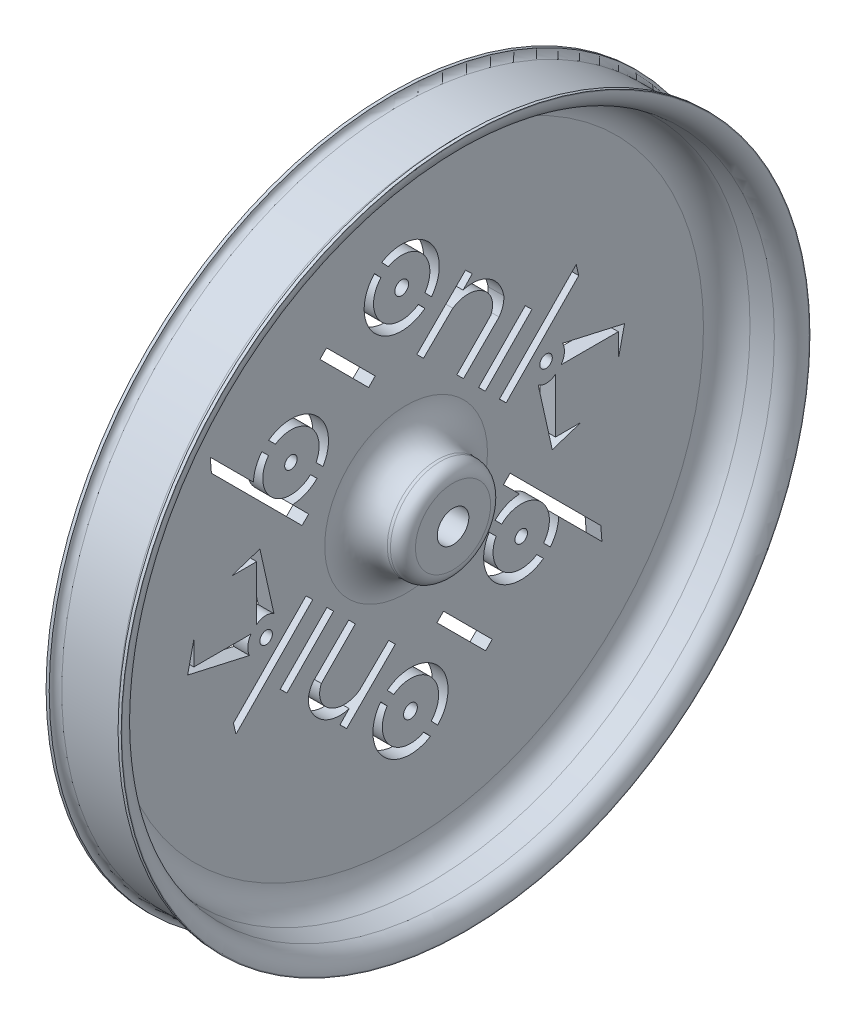
SolidWorks part; units mm, degrees
ref_plane "Płaszczyzna przednia" through (0, 0, 0) normal (0, 0, 1) x (1, 0, 0)
ref_plane "Płaszczyzna górna" through (0, 0, 0) normal (0, 1, 0) x (1, 0, 0)
ref_plane "Płaszczyzna prawa" through (0, 0, 0) normal (1, 0, 0) x (0, 0, -1)
sketch "Szkic1" plane through (0, 0, 0) normal (0, 0, 1) x (1, 0, 0)
  line L0 (7.5, -25.7789) -> (-2.5, -25.7789)
  line L1 (7.5, -25.7789) -> (7.5, -17.7789)
  line L2 (7.5, -17.7789) -> (0, -17.7789)
  line L3 (0, -17.7789) -> (0, 21.719)
  line L4 (-2.5, 29.2211) -> (-2, 29.2211)
  line L5 (9.5, 29.2211) -> (9.5, 29.1143)
  line L6 (9.5, 29.2211) -> (9, 29.2211)
  line L7 (-2, 29.2211) -> (-2, 29.2183)
  line L8 (-1, 28.2183) -> (8, 28.2183)
  line L9 (-2.5, 29.2211) -> (-2.5, -25.7789)
  line L10 (3.4713, 25.6839) -> (6.8965, 26.1406)
  line L11 (9, 29.2183) -> (9, 29.2211)
  arc A0 (-1, 28.2183) -> (-2, 29.2183) centre (-1, 29.2183) cw
  arc A1 (9.5, 29.1143) -> (6.8965, 26.1406) centre (6.5, 29.1143) cw
  arc A2 (0, 21.719) -> (3.4713, 25.6839) centre (4, 21.719) cw
  arc A3 (8, 28.2183) -> (9, 29.2183) centre (8, 29.2183) ccw
  point P10 (9.5, 26.2211)
  point P17 (0, 27.2211)
  dimension "D6" = 0.5
  dimension "D9" = 3
  dimension "D10" = 4
  dimension "D12" = 1
  dimension "D1" = 10
  dimension "D2" = 8
  dimension "D3" = 55
  dimension "D4" = 12
  dimension "D5" = 3
  dimension "D7" = 0.5
  dimension "D8" = 45
  dimension "D11" = 2.5
revolve "Obrót1" add sketch "Szkic1" angle 360 about L0
sketch "Szkic4" plane through (7.5, 0, 0) normal (1, 0, 0) x (0, 0, -1)
  circle A0 centre (0, -25.7789) radius 2.525
  dimension "D1" = 5.05
extrude "Wytnij-wyciągnięcie8" cut sketch "Szkic4" against normal through all
sketch "Szkic5" plane through (0, 0, 0) normal (1, 0, 0) x (0, 0, -1)
  line L0 (112.1629, 275.1146) -> (679.4962, 275.1146) construction
  line L1 (-31.0948, -6.6131) -> (-16.6157, -21.0922)
  line L2 (-16.6157, -21.0922) -> (-15.5551, -20.0316)
  line L3 (-15.5551, -20.0316) -> (-18.1257, -17.4609)
  line L4 (-24.3831, -11.2036) -> (-31.2774, -4.3092)
  line L5 (-31.2774, -4.3092) -> (-31.0948, -6.6131)
  line L6 (-13.7626, 0.4627) -> (-12.702, 1.5234)
  line L7 (-12.702, 1.5234) -> (-4.9238, -6.2548)
  line L8 (-4.9238, -6.2548) -> (-5.9844, -7.3154)
  line L9 (-5.9844, -7.3154) -> (-13.7626, 0.4627)
  line L10 (2.7778, -7.6585) -> (1.7172, -6.5979)
  line L11 (1.7172, -6.5979) -> (9.4953, 1.1803)
  line L12 (9.4953, 1.1803) -> (10.57, 0.1339)
  line L13 (10.57, 0.1339) -> (9.0927, -1.3833)
  line L14 (2.7778, -7.6585) -> (7.4664, -3.0724)
  line L15 (14.8516, -7.9843) -> (9.168, -13.6679)
  line L16 (9.168, -13.6679) -> (8.1073, -12.6072)
  line L17 (8.1073, -12.6072) -> (13.5313, -7.0832)
  line L18 (19.0342, -8.5077) -> (20.1045, -9.5586)
  line L19 (20.1045, -9.5586) -> (12.6512, -17.1495)
  line L20 (12.6512, -17.1495) -> (11.5808, -16.0986)
  line L21 (11.5808, -16.0986) -> (19.0342, -8.5077)
  line L22 (14.91, -19.3675) -> (27.173, -6.8781)
  line L23 (27.173, -6.8781) -> (27.5713, -8.6134)
  line L24 (27.5713, -8.6134) -> (15.9803, -20.4184)
  line L25 (15.9803, -20.4184) -> (14.91, -19.3675)
  line L30 (25.0179, -16.6923) -> (34.8909, -18.9183)
  line L31 (34.8909, -18.9183) -> (33.8934, -23.3427)
  line L32 (33.8934, -23.3427) -> (33.8934, -19.5403)
  line L33 (33.8934, -19.5403) -> (24.7607, -19.5403)
  line L34 (21.1025, -20.5215) -> (23.3499, -30.5953)
  line L35 (23.3499, -30.5953) -> (27.9255, -29.0986)
  line L36 (27.9255, -29.0986) -> (23.865, -29.0986)
  line L37 (23.865, -29.0986) -> (23.865, -20.3921)
  line L38 (-14.2148, -15.7768) -> (-15.2757, -14.716)
  line L39 (-13.2714, -14.599) -> (-14.3731, -13.4973)
  line L40 (-21.9663, -8.7368) -> (-23.0341, -7.669)
  line L41 (-20.8696, -7.7122) -> (-21.9465, -6.6352)
  line L42 (-2.824, 7.8162) -> (-3.8882, 8.9319)
  line L43 (-4.0153, 6.8919) -> (-5.0523, 7.9791)
  line L44 (3.009, 1.3009) -> (4.0611, 0.1978)
  line L45 (1.9645, 0.2227) -> (3.0062, -0.8694)
  arc A0 (-2.824, 7.8162) -> (3.009, 1.3009) centre (-0.7, 3.8491) cw
  circle A1 centre (-18.3888, -11.4667) radius 1
  arc A2 (-4.0153, 6.8919) -> (1.9645, 0.2227) centre (-0.7, 3.8491) ccw
  circle A3 centre (-0.7, 3.8491) radius 1.1
  arc A6 (7.4664, -3.0724) -> (12.8569, -3.5397) centre (9.8742, -6.6212) cw
  arc A7 (9.0927, -1.3833) -> (15.6101, -5.4316) centre (10.5698, -6.2757) cw
  arc A8 (12.8569, -3.5397) -> (13.5313, -7.0832) centre (10.6785, -5.7902) cw
  arc A9 (15.6101, -5.4316) -> (14.8516, -7.9843) centre (11.6962, -5.6576) cw
  circle A10 centre (22.3514, -17.8482) radius 1
  arc A11 (25.0179, -16.6923) -> (24.7607, -19.5403) centre (22.4645, -17.8973) cw
  arc A12 (23.865, -20.3921) -> (21.1025, -20.5215) centre (22.3975, -18.6134) cw
  arc A13 (-23.0341, -7.669) -> (-24.3831, -11.2036) centre (-18.3888, -11.4667) ccw
  arc A14 (-21.9465, -6.6352) -> (-13.2714, -14.599) centre (-18.3888, -11.4667) cw
  arc A15 (-14.3731, -13.4973) -> (-20.8696, -7.7122) centre (-18.3888, -11.4667) ccw
  arc A16 (-21.9663, -8.7368) -> (-15.2757, -14.716) centre (-18.3888, -11.4667) ccw
  arc A17 (-14.2148, -15.7768) -> (-18.1257, -17.4609) centre (-18.3888, -11.4667) cw
  arc A18 (-3.8882, 8.9319) -> (4.0611, 0.1978) centre (-0.7, 3.8491) cw
  arc A19 (-5.0523, 7.9791) -> (3.0062, -0.8694) centre (-0.7, 3.8491) ccw
  point P71 (-1, -15)
  dimension "D11" = 1.5
  dimension "D12" = 2
  dimension "D13" = 2
  dimension "D14" = 1.5
  dimension "D15" = 1.5
  dimension "D19" = 11
  dimension "D23" = 1.5
  dimension "D24" = 1.5
  dimension "D25" = 6
  dimension "D26" = 6
  dimension "D1" = 1.5
  dimension "D2" = 1.5
  dimension "D5" = 1.5
  dimension "D6" = 1.5
  dimension "D7" = 1.5
  dimension "D8" = 1.5
  dimension "D9" = 1.5
  dimension "D10" = 1.5
  dimension "D16" = 1.5
  dimension "D17" = 1.5
  dimension "D18" = 1.5
  dimension "D20" = 11
  dimension "D21" = 10.6384
  dimension "D22" = 1.5
  dimension "D27" = 0.524
extrude "Wytnij-wyciągnięcie9" cut sketch "Szkic5" against normal through all
fillet "Zaokrąglenie1" radius 2 1 edges at (7.5, -25.7789, -8)
sketch "Szkic6" plane through (0, 0, 0) normal (1, 0, 0) x (0, 0, -1)
  line L35 (-20.6685, -60.7541) -> (-20.6685, -65.2374)
  line L36 (-20.6685, -65.2374) -> (-19.6852, -65.2374)
  line L37 (-19.6852, -65.2374) -> (-19.6852, -62.7584)
  line L38 (-19.729, -61.5951) -> (-19.6986, -61.5951)
  line L39 (-19.5465, -62.2204) -> (-18.3908, -65.2374)
  line L40 (-18.3908, -65.2374) -> (-17.4985, -65.2374)
  line L41 (-17.4985, -65.2374) -> (-16.3631, -62.1893)
  line L42 (-16.211, -61.5951) -> (-16.184, -61.5951)
  line L43 (-16.2244, -62.5549) -> (-16.2244, -65.2374)
  line L44 (-16.2244, -65.2374) -> (-15.1462, -65.2374)
  line L45 (-15.1462, -65.2374) -> (-15.1462, -60.7541)
  line L46 (-15.1462, -60.7541) -> (-16.7043, -60.7541)
  line L47 (-16.7043, -60.7541) -> (-17.6946, -63.4053)
  line L48 (-17.8871, -64.0525) -> (-17.9075, -64.0525)
  line L49 (-18.08, -63.4117) -> (-19.0699, -60.7541)
  line L50 (-19.0699, -60.7541) -> (-20.6685, -60.7541)
  line L51 (-12.801, -60.7541) -> (-14.565, -65.2374)
  line L52 (-14.565, -65.2374) -> (-13.3822, -65.2374)
  line L53 (-13.3822, -65.2374) -> (-13.041, -64.2401)
  line L54 (-13.041, -64.2401) -> (-11.3174, -64.2401)
  line L55 (-11.3174, -64.2401) -> (-10.9726, -65.2374)
  line L56 (-10.9726, -65.2374) -> (-9.7831, -65.2374)
  line L57 (-9.7831, -65.2374) -> (-11.5066, -60.7541)
  line L58 (-11.5066, -60.7541) -> (-12.801, -60.7541)
  line L59 (-8.7022, -60.7541) -> (-7.2894, -62.9959)
  line L60 (-7.2894, -62.9959) -> (-8.8338, -65.2374)
  line L61 (-8.8338, -65.2374) -> (-7.5327, -65.2374)
  line L62 (-7.5327, -65.2374) -> (-6.6945, -63.79)
  line L63 (-6.5829, -63.4774) -> (-6.5695, -63.4774)
  line L64 (-6.4716, -63.7776) -> (-5.6367, -65.2374)
  line L65 (-5.6367, -65.2374) -> (-4.3423, -65.2374)
  line L66 (-4.3423, -65.2374) -> (-5.8363, -62.9771)
  line L67 (-5.8363, -62.9771) -> (-4.3828, -60.7541)
  line L68 (-4.3828, -60.7541) -> (-5.5996, -60.7541)
  line L69 (-5.5996, -60.7541) -> (-6.37, -62.0859)
  line L70 (-6.5221, -62.4768) -> (-6.5358, -62.4768)
  line L71 (-6.6812, -62.0987) -> (-7.374, -60.7541)
  line L72 (-7.374, -60.7541) -> (-8.7022, -60.7541)
  line L73 (-2.5549, -60.7541) -> (-2.5549, -65.2374)
  line L74 (-2.5549, -65.2374) -> (-0.693, -65.2374)
  line L75 (-0.0506, -62.8302) -> (-0.0506, -62.8177)
  line L76 (-0.7909, -60.7541) -> (-2.5549, -60.7541)
  line L77 (4.4336, -60.7541) -> (2.6693, -65.2374)
  line L78 (2.6693, -65.2374) -> (3.8521, -65.2374)
  line L79 (3.8521, -65.2374) -> (4.1936, -64.2401)
  line L80 (4.1936, -64.2401) -> (5.9172, -64.2401)
  line L81 (5.9172, -64.2401) -> (6.2618, -65.2374)
  line L82 (6.2618, -65.2374) -> (7.4516, -65.2374)
  line L83 (7.4516, -65.2374) -> (5.728, -60.7541)
  line L84 (5.728, -60.7541) -> (4.4336, -60.7541)
  line L85 (8.877, -60.7541) -> (8.877, -63.3429)
  line L86 (12.8853, -63.2961) -> (12.8853, -60.7541)
  line L87 (12.8853, -60.7541) -> (11.7937, -60.7541)
  line L88 (11.7937, -60.7541) -> (11.7937, -63.3928)
  line L89 (9.9723, -63.3554) -> (9.9723, -60.7541)
  line L90 (9.9723, -60.7541) -> (8.877, -60.7541)
  line L91 (14.9702, -60.7541) -> (14.9702, -65.2374)
  line L92 (14.9702, -65.2374) -> (15.9537, -65.2374)
  line L93 (15.9537, -65.2374) -> (15.9537, -62.7584)
  line L94 (15.9096, -61.5951) -> (15.9401, -61.5951)
  line L95 (16.0921, -62.2204) -> (17.2482, -65.2374)
  line L96 (17.2482, -65.2374) -> (18.1402, -65.2374)
  line L97 (18.1402, -65.2374) -> (19.2759, -62.1893)
  line L98 (19.4279, -61.5951) -> (19.455, -61.5951)
  line L99 (19.4142, -62.5549) -> (19.4142, -65.2374)
  line L100 (19.4142, -65.2374) -> (20.4924, -65.2374)
  line L101 (20.4924, -65.2374) -> (20.4924, -60.7541)
  line L102 (20.4924, -60.7541) -> (18.9343, -60.7541)
  line L103 (18.9343, -60.7541) -> (17.9443, -63.4053)
  line L104 (17.7515, -64.0525) -> (17.7314, -64.0525)
  line L105 (17.559, -63.4117) -> (16.5687, -60.7541)
  line L106 (16.5687, -60.7541) -> (14.9702, -60.7541)
  line L107 (-1.4634, -61.4983) -> (-1.0546, -61.4983)
  line L108 (-0.9834, -62.5613) -> (-1.4634, -62.5613)
  line L109 (-1.4634, -62.5613) -> (-1.4634, -61.4983)
  line L110 (-12.1961, -61.5546) -> (-12.169, -61.5546)
  line L111 (-12.0878, -61.9579) -> (-11.5674, -63.4649)
  line L112 (-11.5674, -63.4649) -> (-12.8077, -63.4649)
  line L113 (-12.8077, -63.4649) -> (-12.2807, -61.9454)
  line L114 (5.0385, -61.5546) -> (5.0656, -61.5546)
  line L115 (5.1465, -61.9579) -> (5.6672, -63.4649)
  line L116 (5.6672, -63.4649) -> (4.4266, -63.4649)
  line L117 (4.4266, -63.4649) -> (4.954, -61.9454)
  line L118 (-1.4634, -63.3116) -> (-0.8651, -63.3116)
  line L119 (-0.8721, -64.4935) -> (-1.4634, -64.4935)
  line L120 (-1.4634, -64.4935) -> (-1.4634, -63.3116)
  spline S29 degree 3 poles (-19.6852, -62.7584) (-19.6863, -62.6412) (-19.6885, -62.3946) (-19.7038, -62.0067) (-19.7203, -61.7363) (-19.729, -61.5951) knots 0 0 0 0 0.302027 0.635343 1 1 1 1
  spline S30 degree 3 poles (-19.6986, -61.5951) (-19.6777, -61.6928) (-19.6418, -61.8605) (-19.5944, -62.07) (-19.5596, -62.1793) (-19.5465, -62.2204) knots 0 0 0 0 0.465921 0.79909 1 1 1 1
  spline S31 degree 3 poles (-16.3631, -62.1893) (-16.3469, -62.1406) (-16.3091, -62.0272) (-16.2606, -61.8282) (-16.2287, -61.6783) (-16.211, -61.5951) knots 0 0 0 0 0.250853 0.584012 1 1 1 1
  spline S32 degree 3 poles (-16.184, -61.5951) (-16.192, -61.7084) (-16.2076, -61.9282) (-16.2215, -62.2483) (-16.2235, -62.455) (-16.2244, -62.5549) knots 0 0 0 0 0.354704 0.68797 1 1 1 1
  spline S33 degree 3 poles (-17.6946, -63.4053) (-17.7173, -63.4698) (-17.7649, -63.6052) (-17.8284, -63.8213) (-17.867, -63.9733) (-17.8871, -64.0525) knots 0 0 0 0 0.303823 0.637003 1 1 1 1
  spline S34 degree 3 poles (-17.9075, -64.0525) (-17.921, -63.9809) (-17.9481, -63.8368) (-18.006, -63.6226) (-18.0552, -63.4824) (-18.08, -63.4117) knots 0 0 0 0 0.329002 0.661877 1 1 1 1
  spline S35 degree 3 poles (-6.6945, -63.79) (-6.6771, -63.7475) (-6.6457, -63.6709) (-6.6071, -63.5669) (-6.5902, -63.5043) (-6.5829, -63.4774) knots 0 0 0 0 0.414756 0.747814 1 1 1 1
  spline S36 degree 3 poles (-6.5695, -63.4774) (-6.5588, -63.521) (-6.5398, -63.5987) (-6.5093, -63.7001) (-6.4828, -63.7546) (-6.4716, -63.7776) knots 0 0 0 0 0.425946 0.758455 1 1 1 1
  spline S37 degree 3 poles (-6.37, -62.0859) (-6.3924, -62.1388) (-6.4329, -62.2345) (-6.4846, -62.3645) (-6.5107, -62.4427) (-6.5221, -62.4768) knots 0 0 0 0 0.410263 0.743484 1 1 1 1
  spline S38 degree 3 poles (-6.5358, -62.4768) (-6.5502, -62.4302) (-6.5778, -62.3406) (-6.6259, -62.2141) (-6.6632, -62.1361) (-6.6812, -62.0987) knots 0 0 0 0 0.360592 0.693428 1 1 1 1
  spline S39 degree 3 poles (-0.693, -65.2374) (-0.5222, -65.2304) (-0.2015, -65.2172) (0.2487, -65.1035) (0.4922, -64.9507) (0.6081, -64.8779) knots 0 0 0 0 0.373882 0.702052 1 1 1 1
  spline S40 degree 3 poles (0.6081, -64.8779) (0.7033, -64.7935) (0.8897, -64.6282) (1.0527, -64.2791) (1.0983, -63.9384) (1.0635, -63.6326) (0.9571, -63.3815) (0.8359, -63.2505) (0.7739, -63.1836) knots 0 0 0 0 0.196043 0.384151 0.584354 0.724031 0.858939 1 1 1 1
  spline S41 degree 3 poles (0.7739, -63.1836) (0.7003, -63.1231) (0.5494, -62.999) (0.264, -62.8813) (0.0574, -62.8477) (-0.0506, -62.8302) knots 0 0 0 0 0.312152 0.640149 1 1 1 1
  spline S42 degree 3 poles (-0.0506, -62.8177) (0.0366, -62.791) (0.2062, -62.739) (0.4375, -62.6115) (0.5631, -62.4963) (0.6252, -62.4393) knots 0 0 0 0 0.348857 0.67836 1 1 1 1
  spline S43 degree 3 poles (0.6252, -62.4393) (0.6783, -62.3781) (0.7819, -62.2587) (0.8732, -62.0373) (0.9041, -61.7787) (0.8637, -61.4951) (0.7078, -61.2193) (0.4508, -61.0073) (0.1088, -60.8572) (-0.3152, -60.7679) (-0.6241, -60.759) (-0.7909, -60.7541) knots 0 0 0 0 0.082794 0.161272 0.24114 0.347886 0.449253 0.558501 0.683554 0.829073 1 1 1 1
  spline S44 degree 3 poles (8.877, -63.3429) (8.902, -63.7261) (8.9478, -64.4281) (9.7681, -65.2358) (10.8627, -65.3596) (11.9652, -65.2343) (12.8118, -64.4089) (12.8594, -63.6886) (12.8853, -63.2961) knots 0 0 0 0 0.174138 0.319064 0.493285 0.672816 0.82168 1 1 1 1
  spline S45 degree 3 poles (11.7937, -63.3928) (11.7841, -63.594) (11.7669, -63.9521) (11.4054, -64.3907) (10.888, -64.4718) (10.3655, -64.3877) (9.9991, -63.9327) (9.9819, -63.5635) (9.9723, -63.3554) knots 0 0 0 0 0.186157 0.331278 0.493092 0.658063 0.807295 1 1 1 1
  spline S46 degree 3 poles (15.9537, -62.7584) (15.9527, -62.6412) (15.9504, -62.3946) (15.9349, -62.0067) (15.9183, -61.7363) (15.9096, -61.5951) knots 0 0 0 0 0.302025 0.635343 1 1 1 1
  spline S47 degree 3 poles (15.9401, -61.5951) (15.961, -61.6928) (15.9969, -61.8605) (16.0442, -62.07) (16.079, -62.1793) (16.0921, -62.2204) knots 0 0 0 0 0.465921 0.79909 1 1 1 1
  spline S48 degree 3 poles (19.2759, -62.1893) (19.2921, -62.1406) (19.3298, -62.0272) (19.3784, -61.8282) (19.4102, -61.6783) (19.4279, -61.5951) knots 0 0 0 0 0.250853 0.584012 1 1 1 1
  spline S49 degree 3 poles (19.455, -61.5951) (19.4469, -61.7084) (19.4313, -61.9282) (19.4172, -62.2483) (19.4152, -62.455) (19.4142, -62.5549) knots 0 0 0 0 0.354705 0.687973 1 1 1 1
  spline S50 degree 3 poles (17.9443, -63.4053) (17.9216, -63.4698) (17.874, -63.6052) (17.8103, -63.8213) (17.7717, -63.9733) (17.7515, -64.0525) knots 0 0 0 0 0.303822 0.63702 1 1 1 1
  spline S51 degree 3 poles (17.7314, -64.0525) (17.718, -63.9809) (17.6908, -63.8368) (17.633, -63.6226) (17.5838, -63.4824) (17.559, -63.4117) knots 0 0 0 0 0.329002 0.661877 1 1 1 1
  spline S52 degree 3 poles (-1.0546, -61.4983) (-0.9058, -61.5032) (-0.6527, -61.5115) (-0.3168, -61.6834) (-0.2429, -61.9528) (-0.2697, -62.1549) (-0.3374, -62.3027) (-0.4507, -62.4192) (-0.6, -62.5033) (-0.782, -62.5535) (-0.9134, -62.5586) (-0.9834, -62.5613) knots 0 0 0 0 0.214019 0.36393 0.502152 0.581744 0.655624 0.731407 0.811388 0.899454 1 1 1 1
  spline S53 degree 3 poles (-12.169, -61.5546) (-12.1632, -61.6044) (-12.1519, -61.6995) (-12.1256, -61.8346) (-12.1, -61.9181) (-12.0878, -61.9579) knots 0 0 0 0 0.364666 0.697373 1 1 1 1
  spline S54 degree 3 poles (-12.2807, -61.9454) (-12.2668, -61.9024) (-12.2393, -61.8172) (-12.2108, -61.6863) (-12.201, -61.5984) (-12.1961, -61.5546) knots 0 0 0 0 0.337951 0.670517 1 1 1 1
  spline S55 degree 3 poles (5.0656, -61.5546) (5.0714, -61.6044) (5.0826, -61.6995) (5.1088, -61.8346) (5.1343, -61.9181) (5.1465, -61.9579) knots 0 0 0 0 0.364696 0.697382 1 1 1 1
  spline S56 degree 3 poles (4.954, -61.9454) (4.9678, -61.9024) (4.9953, -61.8172) (5.0238, -61.6863) (5.0336, -61.5984) (5.0385, -61.5546) knots 0 0 0 0 0.337951 0.670517 1 1 1 1
  spline S57 degree 3 poles (-0.8651, -63.3116) (-0.787, -63.3144) (-0.6412, -63.3195) (-0.44, -63.3699) (-0.2768, -63.4555) (-0.1528, -63.5721) (-0.0778, -63.7215) (-0.0572, -63.8897) (-0.0782, -64.0602) (-0.1538, -64.2168) (-0.2794, -64.34) (-0.4443, -64.4311) (-0.6472, -64.4851) (-0.7938, -64.4906) (-0.8721, -64.4935) knots 0 0 0 0 0.104446 0.194774 0.274999 0.348588 0.41889 0.493869 0.572366 0.645747 0.721977 0.804087 0.89532 1 1 1 1
sketch "Szkic7" plane through (0, 0, 0) normal (1, 0, 0) x (0, 0, -1)
  line L0 (-17.4603, -58.4263) -> (-17.4603, -54.0791)
  line L1 (-16.7503, -53.4132) -> (-14.2301, -54.0581)
  line L2 (-13.7698, -54.7242) -> (-13.7698, -54.7641)
  line L3 (-12.8433, -55.7872) -> (-6.3839, -55.7872)
  line L4 (-5.8713, -53.9113) -> (-8.3671, -52.0829)
  line L5 (-8.8797, -51.9124) -> (-11.4373, -51.9124)
  line L6 (-12.0226, -51.2308) -> (-12.0226, -49.2733)
  line L7 (-11.4373, -48.5916) -> (-8.8797, -48.5916)
  line L8 (-8.3671, -48.421) -> (-5.8713, -46.5928)
  line L9 (-6.3839, -44.7169) -> (-12.8433, -44.7169)
  line L10 (-13.7698, -45.7401) -> (-13.7698, -45.7801)
  line L11 (-14.2301, -46.446) -> (-16.7503, -47.0909)
  line L12 (-17.4603, -46.4248) -> (-17.4603, -42.0778)
  line L13 (-16.8751, -41.396) -> (-2.3518, -41.396)
  line L14 (-1.7668, -42.0778) -> (-1.7668, -47.7836)
  line L15 (-2.1038, -48.401) -> (-3.8125, -49.3352)
  line L16 (-3.8125, -51.1689) -> (-2.1038, -52.1031)
  line L17 (-1.7668, -52.7203) -> (-1.7668, -58.4263)
  line L18 (-2.3518, -59.1081) -> (-16.8751, -59.1081)
  line L25 (12.5072, -46.2896) -> (11.043, -45.1383)
  line L26 (0.5889, -41.2253) -> (6.712, -41.2253)
  line L27 (3.9645, -46.0591) -> (3.9645, -54.4452)
  line L28 (8.9311, -41.2253) -> (11.5375, -41.2253)
  line L29 (12.9545, -54.4452) -> (12.9545, -47.2104)
  line L30 (-0.5824, -58.1073) -> (-0.5824, -42.3968)
  line L31 (8.9311, -44.8876) -> (10.3191, -44.8876)
  line L32 (12.263, -41.4772) -> (17.0556, -45.2579)
  line L33 (17.5015, -46.1776) -> (17.5015, -58.1073)
  line L34 (5.136, -44.8876) -> (6.712, -44.8876)
  line L35 (6.712, -41.2253) -> (6.712, -44.8876)
  line L36 (8.9311, -41.2253) -> (8.9311, -44.8876)
  line L37 (6.712, -55.6165) -> (6.712, -59.2788)
  line L38 (8.9311, -55.6165) -> (8.9311, -59.2788)
  line L39 (5.136, -55.6165) -> (6.712, -55.6165)
  line L40 (8.9311, -55.6165) -> (11.7831, -55.6165)
  line L41 (16.3301, -59.2788) -> (8.9311, -59.2788)
  line L42 (6.712, -59.2788) -> (0.5889, -59.2788)
  spline S0 degree 3 poles (-16.8751, -59.1081) (-16.9789, -59.0879) (-17.1908, -59.0468) (-17.4157, -58.7696) (-17.445, -58.5441) (-17.4603, -58.4263) knots 0 0 0 0 0.314204 0.64159 1 1 1 1
  spline S1 degree 3 poles (-17.4603, -54.0791) (-17.445, -53.9603) (-17.4158, -53.7331) (-17.1921, -53.4681) (-16.9656, -53.3923) (-16.8345, -53.3983) (-16.7921, -53.4035) (-16.7643, -53.41) (-16.7503, -53.4132) knots 0 0 0 0 0.317625 0.607402 0.885007 0.922973 0.961318 1 1 1 1
  spline S2 degree 3 poles (-14.2301, -54.0581) (-14.1457, -54.0952) (-13.9729, -54.1712) (-13.8045, -54.4258) (-13.7816, -54.6226) (-13.7698, -54.7242) knots 0 0 0 0 0.315646 0.646724 1 1 1 1
  spline S3 degree 3 poles (-13.7698, -54.7641) (-13.7452, -54.9417) (-13.6975, -55.285) (-13.3367, -55.6982) (-13.0069, -55.7577) (-12.8433, -55.7872) knots 0 0 0 0 0.350775 0.677934 1 1 1 1
  spline S4 degree 3 poles (-6.3839, -55.7872) (-6.2194, -55.7577) (-5.888, -55.6982) (-5.5401, -55.2851) (-5.4303, -54.8291) (-5.4908, -54.432) (-5.6303, -54.1278) (-5.7914, -53.983) (-5.8713, -53.9113) knots 0 0 0 0 0.195604 0.394266 0.607256 0.741861 0.87198 1 1 1 1
  spline S5 degree 3 poles (-8.3671, -52.0829) (-8.4191, -52.0494) (-8.5221, -51.9829) (-8.698, -51.924) (-8.8191, -51.9162) (-8.8797, -51.9124) knots 0 0 0 0 0.337913 0.669074 1 1 1 1
  spline S6 degree 3 poles (-11.4373, -51.9124) (-11.541, -51.8922) (-11.753, -51.8511) (-11.978, -51.574) (-12.0073, -51.3486) (-12.0226, -51.2308) knots 0 0 0 0 0.31426 0.641681 1 1 1 1
  spline S7 degree 3 poles (-12.0226, -49.2733) (-12.0073, -49.1555) (-11.978, -48.93) (-11.753, -48.6529) (-11.541, -48.6117) (-11.4373, -48.5916) knots 0 0 0 0 0.35832 0.685765 1 1 1 1
  spline S8 degree 3 poles (-8.8797, -48.5916) (-8.8191, -48.5877) (-8.698, -48.58) (-8.5221, -48.5211) (-8.4191, -48.4546) (-8.3671, -48.421) knots 0 0 0 0 0.330905 0.662031 1 1 1 1
  spline S9 degree 3 poles (-5.8713, -46.5928) (-5.7914, -46.521) (-5.6304, -46.3762) (-5.4908, -46.0721) (-5.4303, -45.675) (-5.5401, -45.2191) (-5.8879, -44.8059) (-6.2194, -44.7464) (-6.3839, -44.7169) knots 0 0 0 0 0.128053 0.258158 0.392673 0.605714 0.804392 1 1 1 1
  spline S10 degree 3 poles (-12.8433, -44.7169) (-13.0069, -44.7464) (-13.3367, -44.8059) (-13.6976, -45.2192) (-13.7452, -45.5625) (-13.7698, -45.7401) knots 0 0 0 0 0.322035 0.649183 1 1 1 1
  spline S11 degree 3 poles (-13.7698, -45.7801) (-13.7816, -45.8816) (-13.8045, -46.0784) (-13.9729, -46.3329) (-14.1457, -46.4089) (-14.2301, -46.446) knots 0 0 0 0 0.353204 0.6843 1 1 1 1
  spline S12 degree 3 poles (-16.7503, -47.0909) (-16.7643, -47.0941) (-16.7921, -47.1004) (-16.8344, -47.1057) (-16.9119, -47.1091) (-17.0261, -47.0918) (-17.1652, -47.0254) (-17.2881, -46.9183) (-17.3846, -46.7764) (-17.4485, -46.6069) (-17.4563, -46.4862) (-17.4603, -46.4248) knots 0 0 0 0 0.038338 0.076325 0.113973 0.246125 0.380414 0.52179 0.677489 0.836012 1 1 1 1
  spline S13 degree 3 poles (-17.4603, -42.0778) (-17.445, -41.96) (-17.4157, -41.7345) (-17.1908, -41.4573) (-16.9789, -41.4162) (-16.8751, -41.396) knots 0 0 0 0 0.35841 0.685797 1 1 1 1
  spline S14 degree 3 poles (-2.3518, -41.396) (-2.248, -41.4162) (-2.0362, -41.4573) (-1.8113, -41.7345) (-1.7821, -41.96) (-1.7668, -42.0778) knots 0 0 0 0 0.314134 0.641538 1 1 1 1
  spline S15 degree 3 poles (-1.7668, -47.7836) (-1.7751, -47.8688) (-1.7913, -48.0352) (-1.9102, -48.2602) (-2.0402, -48.3547) (-2.1038, -48.401) knots 0 0 0 0 0.348556 0.680939 1 1 1 1
  spline S16 degree 3 poles (-3.8125, -49.3352) (-3.9108, -49.4046) (-4.1089, -49.5446) (-4.2857, -49.8785) (-4.3488, -50.252) (-4.2857, -50.6256) (-4.1089, -50.9595) (-3.9108, -51.0995) (-3.8125, -51.1689) knots 0 0 0 0 0.162555 0.327554 0.5 0.672446 0.837445 1 1 1 1
  spline S17 degree 3 poles (-2.1038, -52.1031) (-2.0402, -52.1494) (-1.9102, -52.2439) (-1.7914, -52.4688) (-1.7751, -52.6352) (-1.7668, -52.7203) knots 0 0 0 0 0.319126 0.651528 1 1 1 1
  spline S18 degree 3 poles (-1.7668, -58.4263) (-1.7821, -58.5441) (-1.8113, -58.7696) (-2.0362, -59.0468) (-2.248, -59.0879) (-2.3518, -59.1081) knots 0 0 0 0 0.358462 0.685866 1 1 1 1
  spline S19 degree 3 poles (11.043, -45.1383) (10.9713, -45.0891) (10.8282, -44.9912) (10.5788, -44.9049) (10.4059, -44.8934) (10.3191, -44.8876) knots 0 0 0 0 0.334028 0.666006 1 1 1 1
  spline S20 degree 3 poles (5.136, -44.8876) (4.9307, -44.9198) (4.5263, -44.9833) (4.0602, -45.4494) (3.9967, -45.8538) (3.9645, -46.0591) knots 0 0 0 0 0.336657 0.663343 1 1 1 1
  spline S21 degree 3 poles (3.9645, -54.4452) (3.9967, -54.6504) (4.0602, -55.0549) (4.5263, -55.5208) (4.9307, -55.5843) (5.136, -55.6165) knots 0 0 0 0 0.336654 0.663329 1 1 1 1
  spline S22 degree 3 poles (11.7831, -55.6165) (11.9883, -55.5843) (12.3928, -55.5208) (12.8588, -55.0549) (12.9223, -54.6504) (12.9545, -54.4452) knots 0 0 0 0 0.336671 0.663346 1 1 1 1
  spline S23 degree 3 poles (12.9545, -47.2104) (12.9439, -47.0926) (12.9227, -46.8582) (12.7644, -46.5323) (12.5932, -46.3708) (12.5072, -46.2896) knots 0 0 0 0 0.334581 0.665468 1 1 1 1
  spline S24 degree 3 poles (-0.5824, -42.3968) (-0.5502, -42.1915) (-0.4867, -41.7871) (-0.0208, -41.321) (0.3837, -41.2575) (0.5889, -41.2253) knots 0 0 0 0 0.336684 0.663379 1 1 1 1
  spline S25 degree 3 poles (11.5375, -41.2253) (11.6245, -41.2311) (11.798, -41.2427) (12.0478, -41.3295) (12.1912, -41.4278) (12.263, -41.4772) knots 0 0 0 0 0.334034 0.666034 1 1 1 1
  spline S26 degree 3 poles (17.0556, -45.2579) (17.1414, -45.3391) (17.312, -45.5006) (17.4697, -45.826) (17.4908, -46.06) (17.5015, -46.1776) knots 0 0 0 0 0.334553 0.665486 1 1 1 1
  spline S27 degree 3 poles (17.5015, -58.1073) (17.4692, -58.3126) (17.4057, -58.717) (16.9398, -59.1831) (16.5354, -59.2466) (16.3301, -59.2788) knots 0 0 0 0 0.336684 0.663379 1 1 1 1
  spline S28 degree 3 poles (0.5889, -59.2788) (0.3837, -59.2466) (-0.0208, -59.1831) (-0.4867, -58.717) (-0.5502, -58.3126) (-0.5824, -58.1073) knots 0 0 0 0 0.336621 0.663316 1 1 1 1
extrude "Dodanie-wyciągnięcie1" [suppressed] add sketch "Szkic6" along normal blind 0.8
extrude "Wytnij-wyciągnięcie10" [suppressed] cut sketch "Szkic7" against normal through all
fillet "Zaokrąglenie2" [suppressed] radius 0.15
fillet "Zaokrąglenie4" radius 5 1 edges at (0, -25.7789, -8)
pattern_circular "Szyk kołowy1" count 2 over 360 about axis through (0, -25.7789, 0) along (1, 0, 0) of "Wytnij-wyciągnięcie9"
